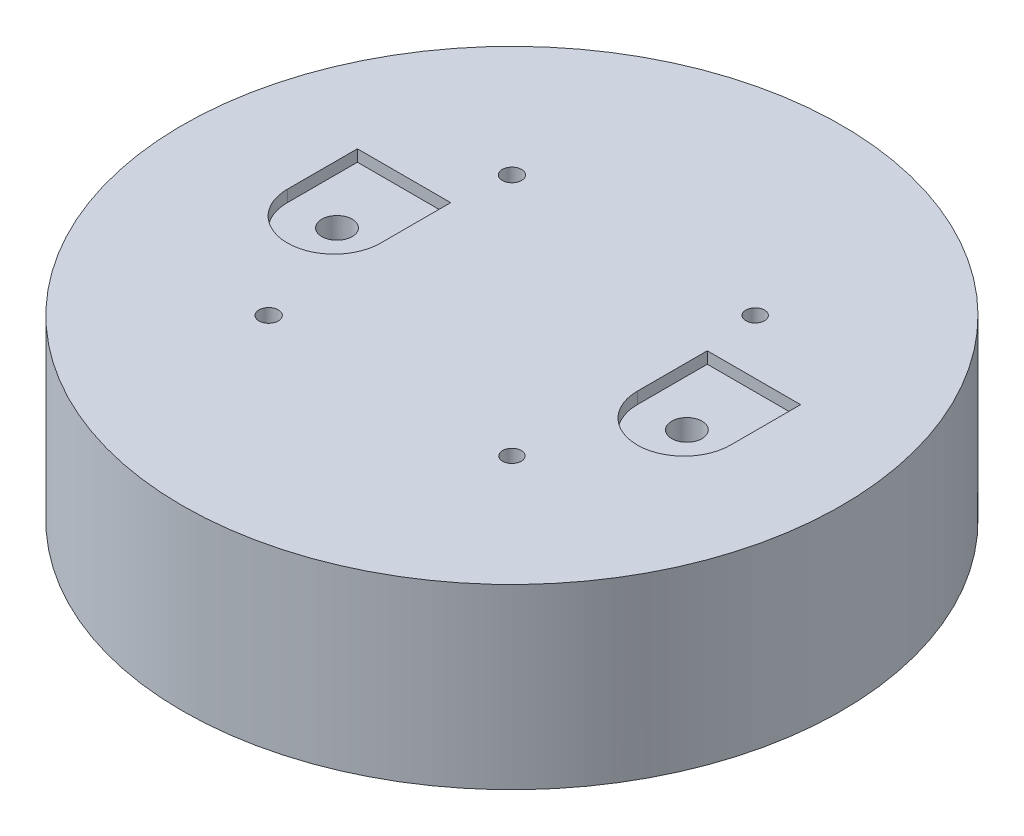
SolidWorks part; units mm, degrees
ref_plane "Front Plane" through (0, 0, 0) normal (0, 0, 1) x (1, 0, 0)
ref_plane "Top Plane" through (0, 0, 0) normal (0, 1, 0) x (1, 0, 0)
ref_plane "Right Plane" through (0, 0, 0) normal (1, 0, 0) x (0, 0, -1)
sketch "Sketch2" plane through (0, 0, 0) normal (0, 1, 0) x (1, 0, 0)
  line L0 (0, 0) -> (0, 56.515)
  circle A0 centre (0, 0) radius 51.435
  circle A1 centre (0, 0) radius 56.515
  circle A2 centre (0, 0) radius 47.2017
  circle A3 centre (0, 0) radius 42.1217
  dimension "D1" = 14.3933
  dimension "D2" = 5.08
  dimension "D3" = 4.2333
  dimension "D4" = 5.08
  dimension "D5" = 102.87
  dimension "D6" = 94.4033
extrude "Boss-Extrude1" add sketch "Sketch2" along normal blind 15.24 contours A1 A0 | A2 A3
sketch "Sketch3" plane through (0, 15.24, 0) normal (0, 1, 0) x (1, 0, 0)
  circle A0 centre (0, 0) radius 56.515
  dimension "D1" = 113.03
extrude "Boss-Extrude2" add sketch "Sketch3" along normal blind 15.24
sketch "Sketch4" plane through (0, 30.48, 0) normal (0, 1, 0) x (1, 0, 0)
  line L0 (0, 37.845) -> (0, -37.845) construction
  line L1 (37.845, 0) -> (-37.845, 0) construction
  line L2 (26.7605, 26.7605) -> (-26.7605, -26.7605) construction
  line L3 (-26.7605, 26.7605) -> (26.7605, -26.7605) construction
  circle A0 centre (0, 0) radius 37.845 construction
  circle A1 centre (0, 0) radius 29.5 construction
  circle A2 centre (20.8597, 20.8597) radius 1.6
  circle A3 centre (20.8597, -20.8597) radius 1.6
  circle A4 centre (-20.8597, -20.8597) radius 1.6588
  circle A5 centre (-20.8597, 20.8597) radius 1.651
  point P7 (0, 0)
  point P10 (0, 0)
  point P13 (0, 0)
  point P16 (0, 0)
  dimension "D1" = 75.69
  dimension "D2" = 59
  dimension "D3" = 45
  dimension "D4" = 45
  dimension "D5" = 3.2
  dimension "D6" = 3.2
  dimension "D7" = 3.3175
  dimension "D8" = 3.302
extrude "Cut-Extrude1" cut sketch "Sketch4" against normal through all both and the other way through all
sketch "Sketch5" plane through (0, 0, 0) normal (0, -1, 0) x (-1, 0, 0)
  line L0 (0, 0) -> (0, 29.5)
  line L1 (13.9476, 25) -> (-13.9476, 25)
  circle A1 centre (0, 0) radius 37.845
  circle A2 centre (0, 0) radius 29.5
  arc A3 (-13.9476, 54.7669) -> (13.9476, 54.7669) centre (0, 0) cw
  circle A4 centre (0, 0) radius 56.515 construction
  point P9 (0, 25)
  dimension "D1" = 75.69
  dimension "D2" = 59
  dimension "D3" = 25
  dimension "D4" = 31.515
ref_plane "Plane1" through (0, 0, -56.515) normal (0, 0, 1) x (1, 0, 0)
sketch "Sketch6" plane through (0, 30.48, 0) normal (0, 1, 0) x (1, 0, 0)
  line L0 (0, 0) -> (0, 56.515) construction
  line L1 (0, 0) -> (0, -56.515) construction
  line L2 (-56.515, 0) -> (56.515, 0) construction
  circle A0 centre (0, 0) radius 56.515 construction
  circle A1 centre (0, 30.48) radius 2.6
  circle A2 centre (0, -30.48) radius 2.6
  point P10 (0, 0)
  dimension "D2" = 5.2
  dimension "D3" = 5.2
  dimension "D1" = 113.03
  dimension "D4" = 30.48
  dimension "D5" = 30.48
ref_plane "Plane3" through (0, 0, -47.244) normal (0, 0, 1) x (1, 0, 0)
ref_plane "Plane4" through (17.78, 0, 0) normal (1, 0, 0) x (0, 0, -1)
sketch "Sketch13" plane through (0, 0, -56.515) normal (0, 0, 1) x (1, 0, 0)
  line L0 (0, 0) -> (0, 32.5704) construction
sketch "Sketch14" plane through (0, 0, -56.515) normal (0, 0, 1) x (1, 0, 0)
  line L0 (0, 0) -> (0, 30.48) construction
  line L1 (-56.515, 0) -> (56.515, 0) construction
  line L2 (56.515, 30.48) -> (-56.515, 30.48) construction
  line L3 (0, 15.24) -> (-5.7214, 15.24) construction
  circle A0 centre (0, 5.08) radius 10
  dimension "D3" = 20
  dimension "D1" = 15.24
  dimension "D2" = 10.16
extrude "Cut-Extrude7" cut sketch "Sketch14" along normal blind 19.558
sketch "Sketch16" plane through (0, 0, -56.515) normal (0, 0, 1) x (1, 0, 0)
  line L0 (0, 0) -> (0, 15.24) construction
  line L1 (0, 5.08) -> (0, 15.24) construction
  line L3 (0, 0) -> (0, 1.27)
  line L4 (9.2458, 1.27) -> (-9.2458, 1.27)
  arc A1 (9.2458, 1.27) -> (-9.2458, 1.27) centre (0, 5.08) ccw
  point P12 (0, 1.27)
  dimension "D1" = 10.16
  dimension "D2" = 1.27
  dimension "D3" = 15.24
extrude "Extrude-Thin1" add sketch "Sketch16" along normal blind 15.24 thin thin type one direction wall 1.27
sketch "Sketch20" plane through (0, 0, 0) normal (0, -1, 0) x (-1, 0, 0)
  circle A0 centre (0, 0) radius 56.515
extrude "Cut-Extrude-Thin3" cut sketch "Sketch20" against normal blind 15.748 thin
sketch "Sketch21" plane through (0, 0, -56.515) normal (0, 0, 1) x (1, 0, 0)
  line L0 (-9.3037, 0) -> (-9.2458, 1.27)
  line L1 (-56.515, 0) -> (56.515, 0) construction
  line L2 (-9.2458, 1.27) -> (9.2458, 1.27)
  line L3 (9.2458, 1.27) -> (-9.2458, 1.27) construction
  line L4 (9.2458, 1.27) -> (9.2458, 0)
  line L5 (9.2458, 0) -> (-9.3037, 0)
  arc A0 (8.6136, 0) -> (8.4029, 10.5013) centre (0, 5.08) ccw construction
extrude "Cut-Extrude12" cut sketch "Sketch21" along normal blind 15.748
sketch "Sketch32" plane through (0, 30.48, 0) normal (0, 1, 0) x (1, 0, 0)
  line L0 (0, 56.515) -> (0, -56.515) construction
  line L1 (-56.515, 0) -> (56.515, 0) construction
  line L2 (-30, 0.5) -> (-30, 0) construction
  line L5 (-22, 11.5) -> (-38, 11.5)
  line L6 (-22, -0.5) -> (-22, 11.5)
  line L7 (30, 0.5) -> (30, 0) construction
  line L12 (38, -0.5) -> (38, 11.5)
  line L13 (22, -0.5) -> (22, 11.5)
  line L14 (22, 11.5) -> (38, 11.5)
  line L15 (-38, -0.5) -> (-38, 11.5)
  circle A0 centre (0, 0) radius 56.515 construction
  circle A5 centre (30, 0) radius 2.6
  arc A7 (22, -0.5) -> (38, -0.5) centre (30, -0.5) ccw
  arc A10 (-22, -0.5) -> (-38, -0.5) centre (-30, -0.5) cw
  circle A11 centre (-30, 0) radius 2.6
extrude "Cut-Extrude18" cut sketch "Sketch32" against normal blind 2
sketch "Sketch33" plane through (0, 30.48, 0) normal (0, 1, 0) x (1, 0, 0)
  circle A0 centre (-30, 0) radius 2.6
  circle A1 centre (30, 0) radius 2.6
extrude "Cut-Extrude19" cut sketch "Sketch33" against normal through all both and the other way through all
sketch "Sketch34" plane through (0, 15.24, 0) normal (0, -1, 0) x (-1, 0, 0)
  circle A0 centre (30, 0) radius 6
  circle A1 centre (-30, 0) radius 6
  dimension "D1" = 12
  dimension "D2" = 12
extrude "Cut-Extrude20" cut sketch "Sketch34" against normal blind 5
sketch "Sketch35" plane through (0, 20.24, 0) normal (0, -1, 0) x (-1, 0, 0)
  circle A0 centre (30, 0) radius 4.5219
